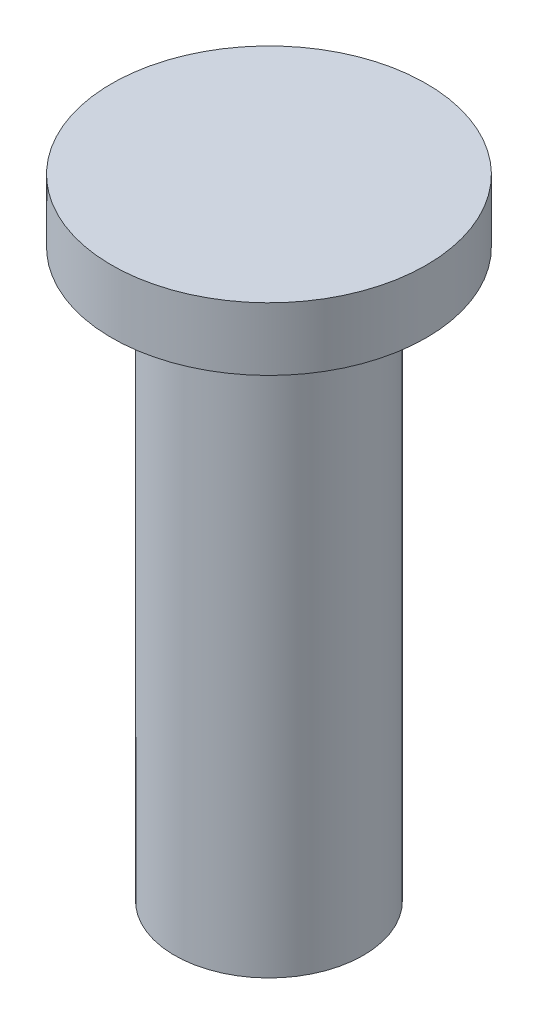
SolidWorks part; units mm, degrees
ref_plane "Front Plane" through (0, 0, 0) normal (0, 0, 1) x (1, 0, 0)
ref_plane "Top Plane" through (0, 0, 0) normal (0, 1, 0) x (1, 0, 0)
ref_plane "Right Plane" through (0, 0, 0) normal (1, 0, 0) x (0, 0, -1)
sketch "Sketch1" plane through (0, 0, 0) normal (0, 0, 1) x (1, 0, 0)
  line L0 (0, -1.2692) -> (0, 8.7308)
  line L1 (0, 8.7308) -> (-2.5, 8.7308)
  line L2 (-2.5, 8.7308) -> (-2.5, 7.7308)
  line L3 (-2.5, 7.7308) -> (-1.5, 7.7308)
  line L4 (-1.5, 7.7308) -> (-1.5, -1.2692)
  line L5 (-1.5, -1.2692) -> (0, -1.2692)
  dimension "D1" = 1
  dimension "D2" = 9
  dimension "D3" = 1.5
  dimension "D4" = 2.5
revolve "Revolve1" add sketch "Sketch1" angle 360 about L0
